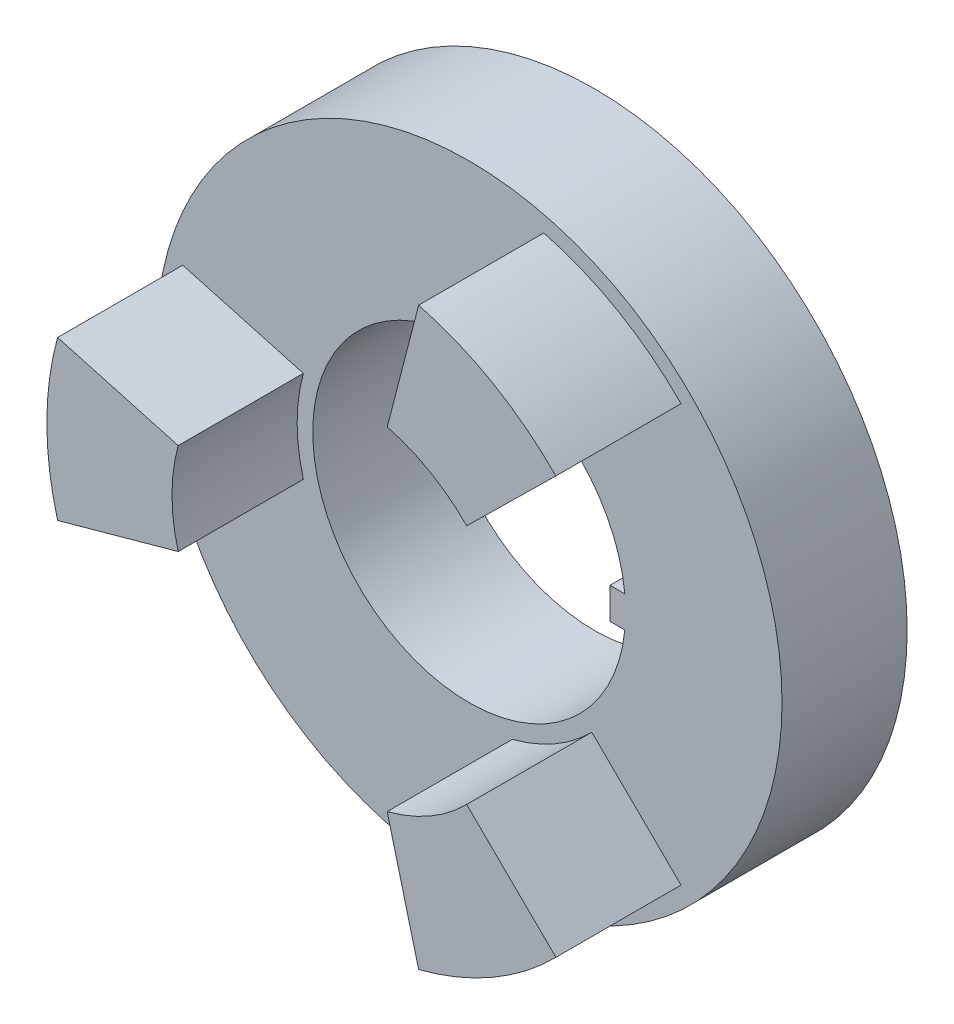
SolidWorks part; units mm, degrees
ref_plane "Front Plane" through (0, 0, 0) normal (0, 0, 1) x (1, 0, 0)
ref_plane "Top Plane" through (0, 0, 0) normal (0, 1, 0) x (1, 0, 0)
ref_plane "Right Plane" through (0, 0, 0) normal (1, 0, 0) x (0, 0, -1)
sketch "Sketch1" plane through (0, 0, 0) normal (0, 0, 1) x (1, 0, 0)
  circle A0 centre (0, 0) radius 10
  circle A1 centre (0, 0) radius 5
  dimension "D1" = 20
  dimension "D2" = 10
extrude "Boss-Extrude2" add sketch "Sketch1" along normal blind 4
sketch "Sketch2" plane through (0, 0, 4) normal (0, 0, 1) x (1, 0, 0)
  line L0 (-10, 0) -> (-9.5, 0)
  line L1 (-5.3008, 1.4667) -> (-9.156, 2.5333)
  line L2 (-5.3008, -1.4667) -> (-9.156, -2.5333)
  line L3 (-5.5, 0) -> (-5, 0)
  line L4 (3.9206, 3.8573) -> (6.7719, 6.6627)
  line L5 (1.3802, 5.324) -> (2.3841, 9.196)
  line L6 (1.3802, -5.324) -> (2.3841, -9.196)
  line L7 (3.9206, -3.8573) -> (6.7719, -6.6627)
  circle A0 centre (0, 0) radius 10 construction
  circle A1 centre (0, 0) radius 5 construction
  circle A3 centre (0, 0) radius 9.5
  circle A4 centre (0, 0) radius 5.5
  point P27 (0, 0)
  dimension "D1" = 3
extrude "Boss-Extrude3" add sketch "Sketch2" along normal blind 4 contours A4 L1 A3 L2 | A4 L6 A3 L7 | A4 L4 A3 L5
ref_plane "Plane1" through (4.578, 7.9293, 0) normal (0.5, 0.866, 0) x (0.866, -0.5, 0)
sketch "Sketch3" plane through (0, 0, 0) normal (0, 0, -1) x (-1, 0, 0)
  line L1 (-5.5, 0.5) -> (-4.5, 0.5)
  line L2 (-5.5, 0.5) -> (-5.5, -0.5)
  line L3 (-5.5, -0.5) -> (-4.5, -0.5)
  line L4 (-4.5, 0.5) -> (-4.5, -0.5)
  line L5 (-5.5, 0.5) -> (-4.5, -0.5) construction
  line L6 (-5.5, -0.5) -> (-4.5, 0.5) construction
  circle A0 centre (0, 0) radius 5 construction
  point P0 (-5, 0)
  dimension "D1" = 1
  dimension "D2" = 1
extrude "Boss-Extrude4" add sketch "Sketch3" against normal blind 4
